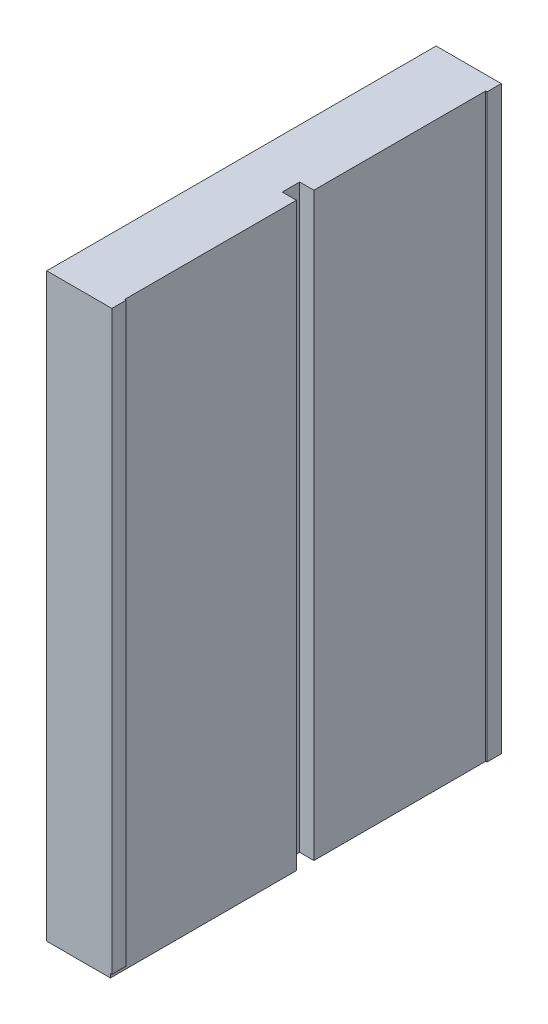
SolidWorks part; units mm, degrees
ref_plane "Front Plane" through (0, 0, 0) normal (0, 0, 1) x (1, 0, 0)
ref_plane "Top Plane" through (0, 0, 0) normal (0, 1, 0) x (1, 0, 0)
ref_plane "Right Plane" through (0, 0, 0) normal (1, 0, 0) x (0, 0, -1)
sketch "Sketch1" plane through (0, 0, 0) normal (0, 1, 0) x (1, 0, 0)
  line L1 (-4.5, 27.5) -> (4.5, 27.5)
  line L2 (-4.5, 27.5) -> (-4.5, -27.5)
  line L3 (-4.5, -27.5) -> (4.5, -27.5)
  line L4 (4.5, 27.5) -> (4.5, -27.5)
  line L5 (-4.5, 27.5) -> (4.5, -27.5) construction
  line L6 (-4.5, -27.5) -> (4.5, 27.5) construction
  point P0 (0, 0)
  dimension "D1" = 9
  dimension "D2" = 55
extrude "Boss-Extrude1" add sketch "Sketch1" along normal blind 82
sketch "Sketch2" plane through (4.5, 0, 0) normal (1, 0, 0) x (0, 0, -1)
  line L0 (0, 82) -> (0, 0)
  line L1 (-27.5, 82) -> (27.5, 82) construction
  line L2 (-27.5, 0) -> (27.5, 0) construction
  line L4 (-1.2308, 82) -> (1.2308, 82)
  line L5 (-1.2308, 82) -> (-1.2308, 0)
  line L6 (-1.2308, 0) -> (1.2308, 0)
  line L7 (1.2308, 82) -> (1.2308, 0)
  line L8 (-1.2308, 82) -> (1.2308, 0) construction
  line L9 (-1.2308, 0) -> (1.2308, 82) construction
  point P6 (0, 41)
  line M1 (-27.5, 0) -> (27.5, 0)
  line M3 (27.5, 82) -> (-27.5, 82)
extrude "Cut-Extrude1" cut sketch "Sketch2" against normal blind 2 contours L5 L0 M3 M1 | L7 L0 M3 M1
sketch "Sketch3" plane through (4.5, 0, 0) normal (1, 0, 0) x (0, 0, -1)
  line L0 (-27.5, 82) -> (-25.5, 82)
  line L1 (-27.5, 82) -> (-1.2308, 82) construction
  line L2 (27.5, 82) -> (25.5, 82)
  line L3 (1.2308, 82) -> (27.5, 82) construction
  line L4 (-27.5, 82) -> (-25.5, 82)
  line L5 (-27.5, 82) -> (-27.5, 0.5454)
  line L6 (-25.5, 82) -> (-25.5, 0.5454)
  line L7 (-27.5, 0.5454) -> (-25.5, 0.5454)
  line L8 (27.5, 82) -> (25.5, 82)
  line L9 (27.5, 82) -> (27.5, 0.0186)
  line L10 (25.5, 82) -> (25.5, 0.0186)
  line L11 (27.5, 0.0186) -> (25.5, 0.0186)
  line M13 (-1.2308, 82) -> (-27.5, 82)
  line M14 (-27.5, 82) -> (-27.5, 0)
  dimension "D1" = 2
  dimension "D2" = 2
extrude "Boss-Extrude2" add sketch "Sketch3" along normal blind 0.2 contours L7 L6 M14 M13 | L11 L9 L2 L10
